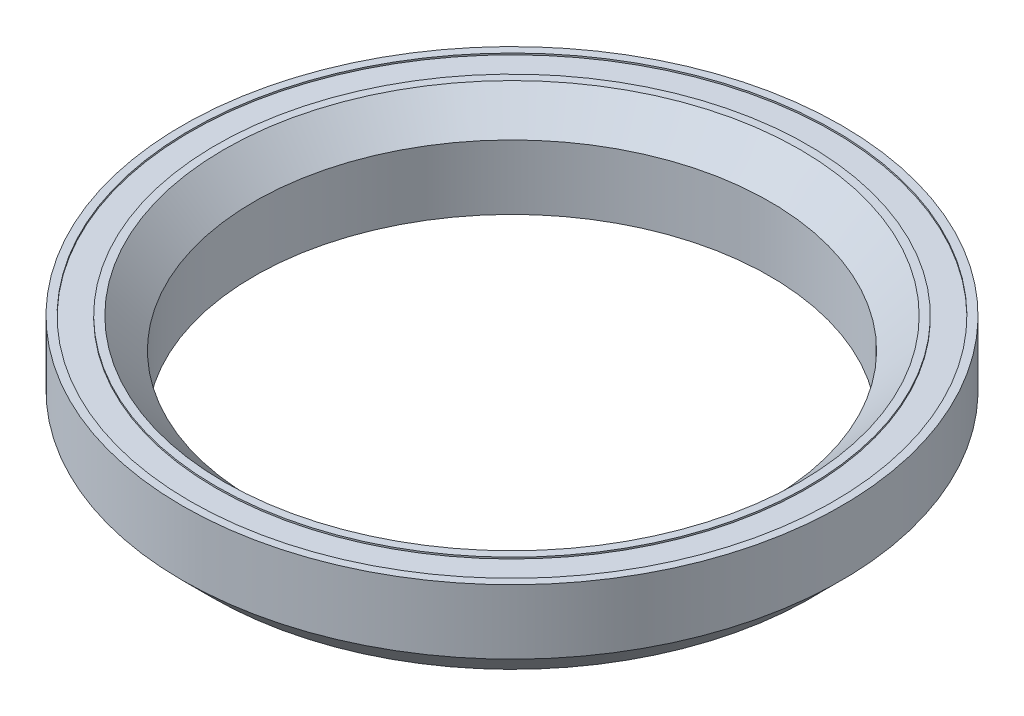
SolidWorks part; units mm, degrees
material "6061-T6 (SS)"
ref_plane "前视基准面" through (0, 0, 0) normal (0, 0, 1) x (1, 0, 0)
ref_plane "上视基准面" through (0, 0, 0) normal (0, 1, 0) x (1, 0, 0)
ref_plane "右视基准面" through (0, 0, 0) normal (1, 0, 0) x (0, 0, -1)
sketch "草图2" plane through (0, 0, 0) normal (1, 0, 0) x (0, 0, -1)
  line L0 (0, 0) -> (0, -23917.3954) construction
  line L1 (0, 0) -> (-23917.3954, 0) construction
  line L3 (-20.9, 1.91) -> (-20.9, 6)
  line L4 (-20.9, 6) -> (-18.26, 6)
  line L6 (-16.35, 4.09) -> (-16.35, 0)
  line L7 (-16.35, 0) -> (-18.99, 0)
  line L8 (-18.99, 0) -> (-20.9, 1.91)
  line L9 (-18.26, 6) -> (-16.35, 4.09)
  dimension "D1" = 6
  dimension "D2" = 16.35
  dimension "D3" = 20.9
  dimension "D4" = 18.99
  dimension "45" = 45
revolve "旋转1" add sketch "草图2" angle 360 about L0
sketch "草图3" plane through (0, 6, 0) normal (0, 1, 0) x (1, 0, 0)
  circle A0 centre (0, 0) radius 18.76
  circle A1 centre (0, 0) radius 20.4
  circle A2 centre (0, 0) radius 20.9 construction
  circle A3 centre (0, 0) radius 18.26 construction
  dimension "D1" = 0.5
  dimension "D2" = 0.5
extrude "切除-拉伸1" cut sketch "草图3" against normal blind 0.1
sketch "草图4" plane through (0, 0, 0) normal (0, -1, 0) x (1, 0, 0)
  circle A0 centre (0, 0) radius 16.85
  circle A1 centre (0, 0) radius 18.49
  circle A2 centre (0, 0) radius 16.35 construction
  circle A3 centre (0, 0) radius 18.99 construction
  dimension "D1" = 0.5
  dimension "D2" = 0.5
extrude "切除-拉伸2" cut sketch "草图4" against normal blind 0.1
move or copy body "实体-移动/复制1" [suppressed] bodies to move or copy 108
